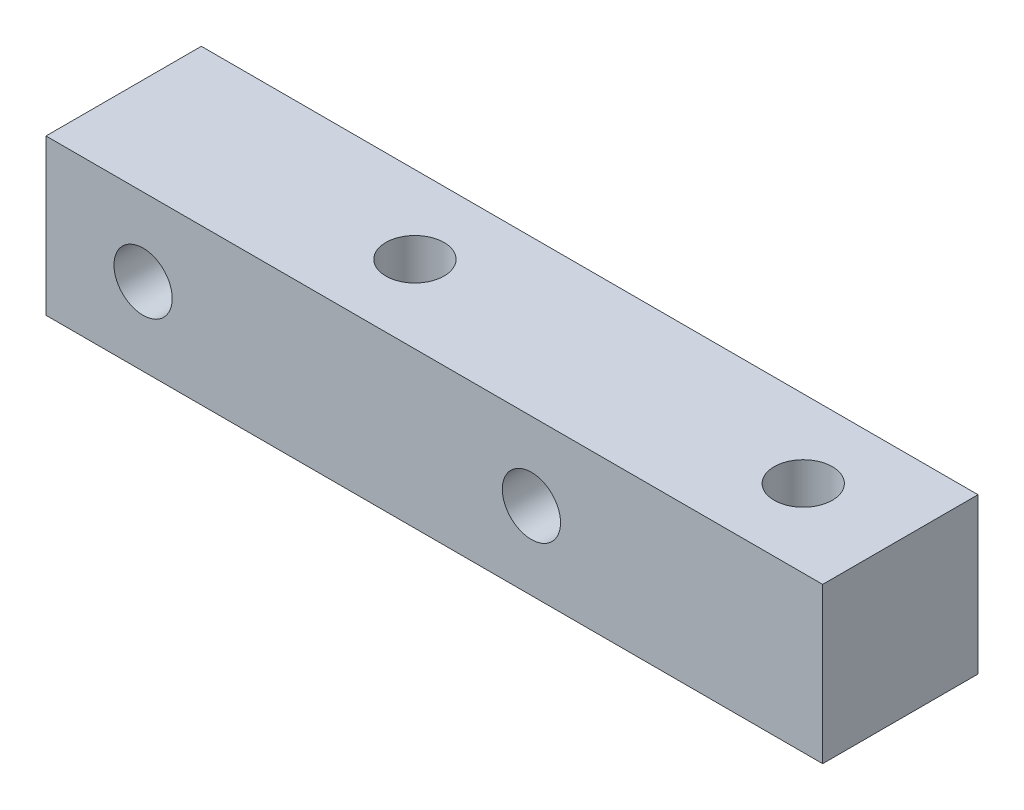
SolidWorks part; units mm, degrees
ref_plane "前视基准面" through (0, 0, 0) normal (0, 0, 1) x (1, 0, 0)
ref_plane "上视基准面" through (0, 0, 0) normal (0, 1, 0) x (1, 0, 0)
ref_plane "右视基准面" through (0, 0, 0) normal (1, 0, 0) x (0, 0, -1)
other "Configuration Table"
sketch "草图1" plane through (0, 0, 0) normal (0, 1, 0) x (1, 0, 0)
  line L0 (20, 0) -> (-20, 0) construction
  line L1 (-20, 4) -> (20, 4)
  line L2 (-20, 4) -> (-20, -4)
  line L3 (-20, -4) -> (20, -4)
  line L4 (20, 4) -> (20, -4)
  line L5 (-20, 4) -> (20, -4) construction
  line L6 (-20, -4) -> (20, 4) construction
  circle A0 centre (15, 0) radius 1.5
  circle A1 centre (-5, 0) radius 1.5
  point P0 (0, 0)
  dimension "D3" = 3
  dimension "D4" = 3
  dimension "D1" = 40
  dimension "D2" = 8
  dimension "D5" = 5
  dimension "D6" = 20
extrude "凸台-拉伸1" add sketch "草图1" along normal blind 8
sketch "草图2" plane through (0, 0, 4) normal (0, 0, 1) x (1, 0, 0)
  line L0 (-20, 4) -> (20, 4) construction
  line L1 (-20, 8) -> (-20, 0) construction
  line L2 (20, 8) -> (20, 0) construction
  circle A0 centre (-15, 4) radius 1.5
  circle A1 centre (5, 4) radius 1.5
  dimension "D1" = 3
  dimension "D2" = 3
  dimension "D3" = 5
  dimension "D4" = 20
extrude "切除-拉伸1" cut sketch "草图2" against normal blind 8
